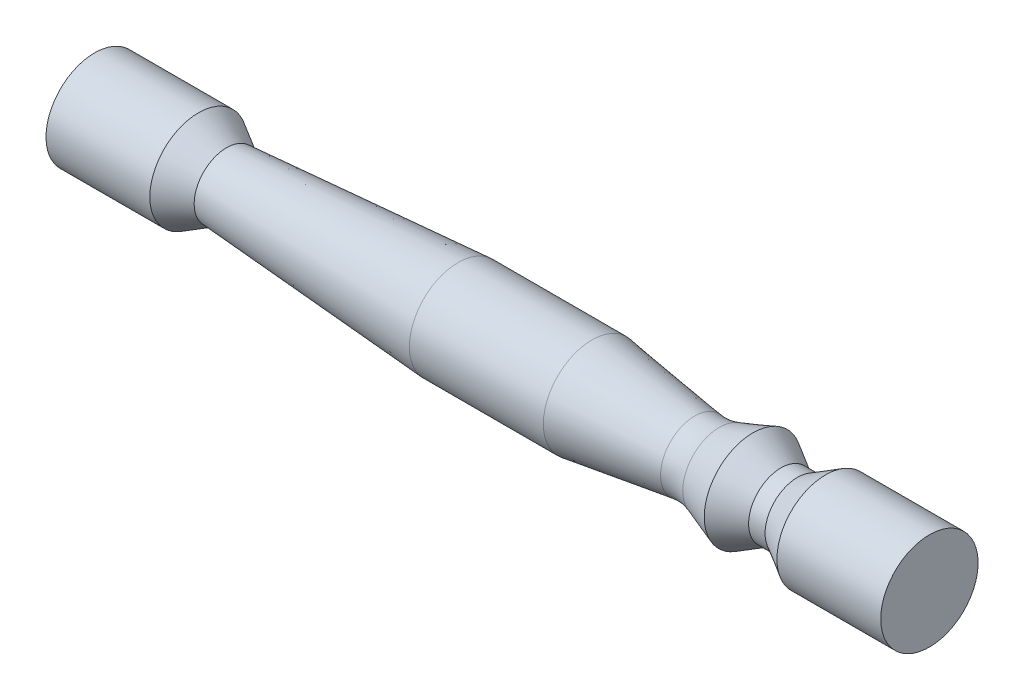
SolidWorks part; units mm, degrees
ref_plane "Front Plane" through (0, 0, 0) normal (0, 0, 1) x (1, 0, 0)
ref_plane "Top Plane" through (0, 0, 0) normal (0, 1, 0) x (1, 0, 0)
ref_plane "Right Plane" through (0, 0, 0) normal (1, 0, 0) x (0, 0, -1)
sketch "Sketch1" plane through (0, 0, 0) normal (0, 0, 1) x (1, 0, 0)
  line L0 (-40.8432, 0) -> (40.8432, 0)
  line L1 (40.8432, 0) -> (40.8432, 4.7625)
  line L2 (40.8432, 4.7625) -> (30.6832, 4.7625)
  line L3 (30.6832, 4.7625) -> (27.9336, 3.175)
  line L4 (27.9336, 3.175) -> (26.3208, 3.175)
  line L5 (26.3208, 3.175) -> (23.5712, 4.7625)
  line L6 (7.8232, 4.7625) -> (-5.2832, 4.7625)
  line L7 (-5.2832, 4.7625) -> (-27.9336, 3.175)
  line L8 (-27.9336, 3.175) -> (-30.6832, 4.7625)
  line L9 (-30.6832, 4.7625) -> (-40.8432, 4.7625)
  line L10 (-40.8432, 4.7625) -> (-40.8432, 0)
  line L11 (7.8232, 4.7625) -> (19.1188, 3.175)
  line L12 (19.1188, 3.175) -> (23.5712, 4.7625)
  dimension "D7" = 17.272
  dimension "D1" = 4.7625
  dimension "D2" = 4.7625
  dimension "D3" = 3.175
  dimension "D4" = 35.56
  dimension "D5" = 81.6864
  dimension "D6" = 10.16
  dimension "D8" = 33.02
  dimension "D9" = 30
  dimension "D10" = 30
  dimension "D11" = 3.175
  dimension "D12" = 10.16
  dimension "D13" = 3.175
  dimension "D14" = 8
revolve "Revolve1" add sketch "Sketch1" angle 360 about L0
fillet "Fillet1" radius 5.08 1 edges at (19.1188, 0, 3.175)
